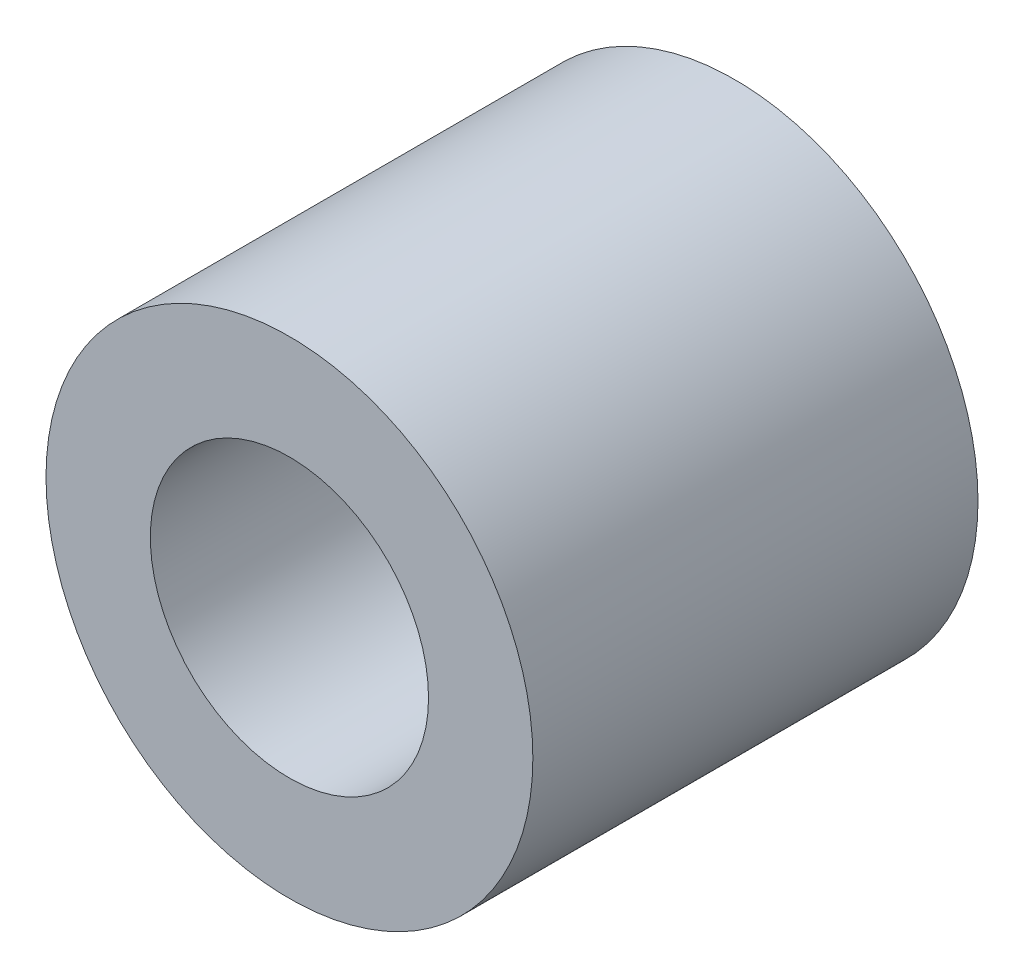
SolidWorks part; units mm, degrees
ref_plane "Front Plane" through (0, 0, 0) normal (0, 0, 1) x (1, 0, 0)
ref_plane "Top Plane" through (0, 0, 0) normal (0, 1, 0) x (1, 0, 0)
ref_plane "Right Plane" through (0, 0, 0) normal (1, 0, 0) x (0, 0, -1)
sketch "Sketch1" plane through (0, 0, 0) normal (0, 0, 1) x (1, 0, 0)
  circle A0 centre (0, 0) radius 2
  circle A1 centre (0, 0) radius 3.5
  dimension "D1" = 4
  dimension "D2" = 7
extrude "Boss-Extrude1" add sketch "Sketch1" along normal blind 6.4
